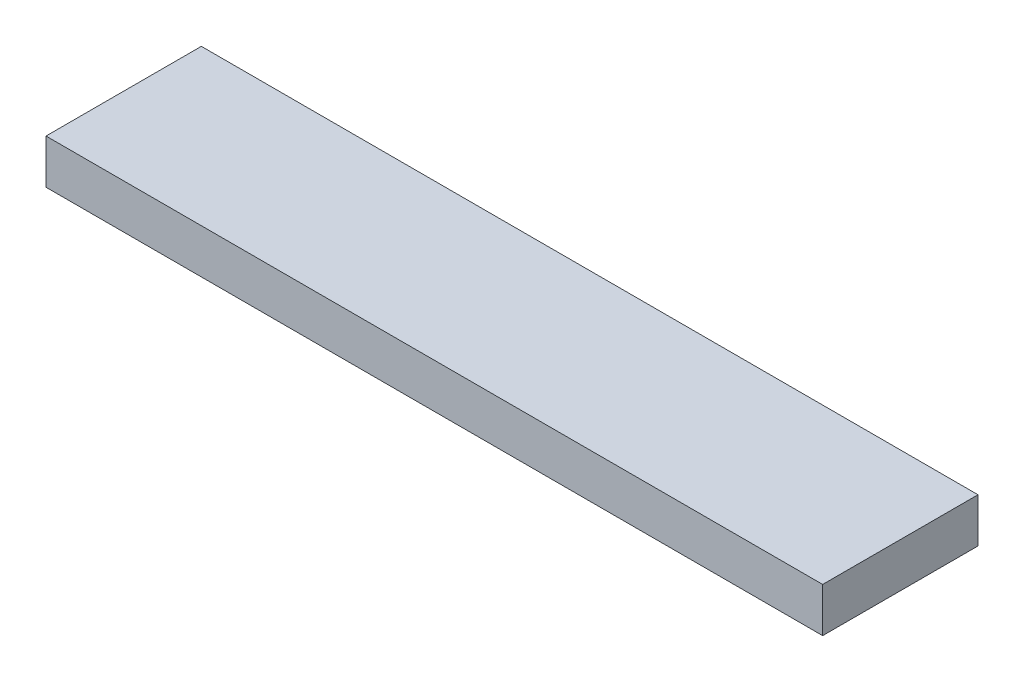
SolidWorks part; units mm, degrees
ref_plane "Front Plane" through (0, 0, 0) normal (0, 0, 1) x (1, 0, 0)
ref_plane "Top Plane" through (0, 0, 0) normal (0, 1, 0) x (1, 0, 0)
ref_plane "Right Plane" through (0, 0, 0) normal (1, 0, 0) x (0, 0, -1)
sketch "Sketch1" plane through (0, 0, 0) normal (0, 1, 0) x (1, 0, 0)
  line L1 (17.5, -3.5) -> (-17.5, -3.5)
  line L2 (17.5, -3.5) -> (17.5, 3.5)
  line L3 (17.5, 3.5) -> (-17.5, 3.5)
  line L4 (-17.5, -3.5) -> (-17.5, 3.5)
  line L5 (17.5, -3.5) -> (-17.5, 3.5) construction
  line L6 (17.5, 3.5) -> (-17.5, -3.5) construction
  point P0 (0, 0)
  dimension "D1" = 35
  dimension "D2" = 7
extrude "Boss-Extrude1" add sketch "Sketch1" along normal blind 2
